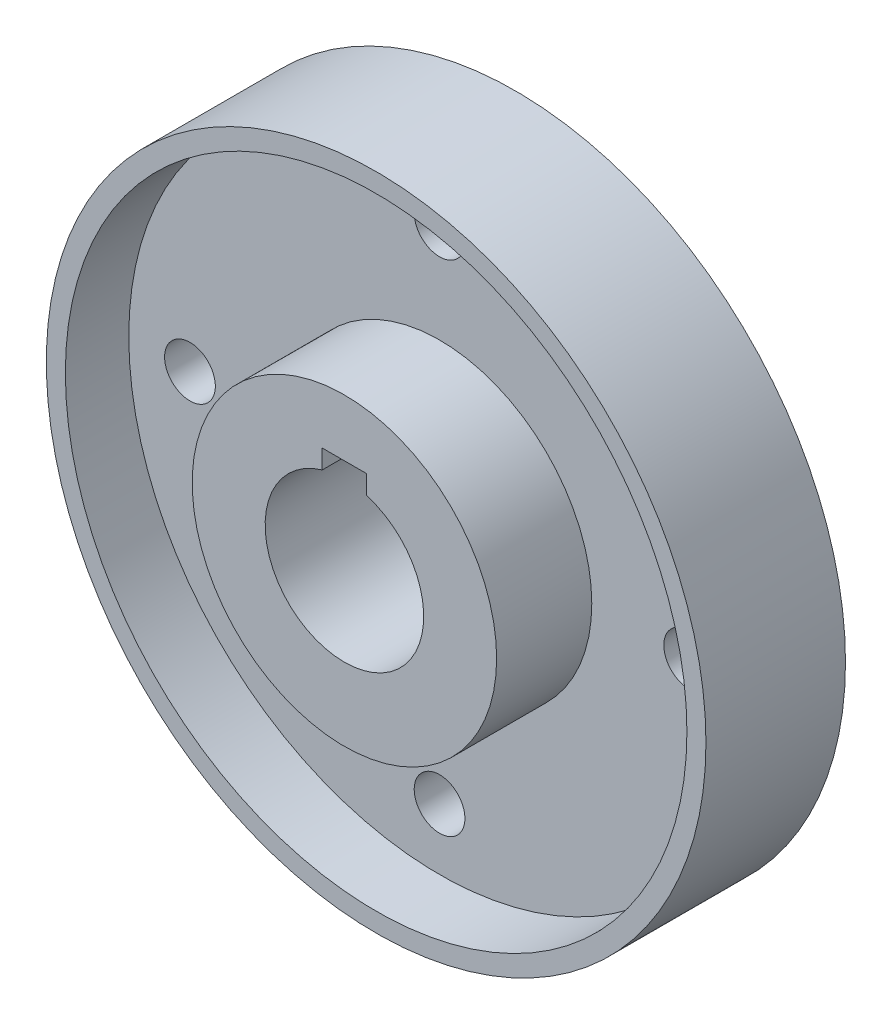
SolidWorks part; units mm, degrees
ref_plane "Front Plane" through (0, 0, 0) normal (0, 0, 1) x (1, 0, 0)
ref_plane "Top Plane" through (0, 0, 0) normal (0, 1, 0) x (1, 0, 0)
ref_plane "Right Plane" through (0, 0, 0) normal (1, 0, 0) x (0, 0, -1)
sketch "Sketch1" plane through (0, 0, 0) normal (1, 0, 0) x (0, 0, -1)
  line L0 (-44, 104) -> (0, 104)
  line L1 (0, 55) -> (0, -55) construction
  line L2 (0, 104) -> (0, 48)
  line L3 (0, 48) -> (3, 48)
  line L4 (3, 48) -> (3, 25)
  line L5 (3, 25) -> (-54, 25)
  line L6 (-54, 25) -> (-54, 48)
  line L7 (-54, 48) -> (-24, 48)
  line L8 (-24, 48) -> (-24, 98)
  line L9 (-24, 98) -> (-44, 98)
  line L10 (-44, 98) -> (-44, 104)
  line L11 (55, 0) -> (-55, 0) construction
  line L12 (-52.4965, 0) -> (46.7439, 0) construction
  dimension "D1" = 6
  dimension "D2" = 20
  dimension "D3" = 3
  dimension "D4" = 30
  dimension "D5" = 48
  dimension "D6" = 25
  dimension "D7" = 48
  dimension "D8" = 50
  dimension "D9" = 44
revolve "Revolve1" add sketch "Sketch1" angle 360 about L12
sketch "Sketch2" plane through (0, 0, 0) normal (0, 0, 1) x (1, 0, 0)
  line L0 (0, -55) -> (0, 55) construction
  line L1 (-7, 30) -> (7, 30)
  line L2 (-7, 30) -> (-7, 20)
  line L3 (-7, 20) -> (7, 20)
  line L4 (7, 30) -> (7, 20)
  line L5 (-7, 30) -> (7, 20) construction
  line L6 (-7, 20) -> (7, 30) construction
  circle A0 centre (0, 0) radius 25 construction
  point P0 (0, 25)
  dimension "D1" = 14
  dimension "D2" = 10
extrude "Cut-Extrude1" cut sketch "Sketch2" along normal mid plane 146
sketch "Sketch3" plane through (0, 0, 0) normal (0, 0, 1) x (1, 0, 0)
  line L0 (0, -29.7) -> (0, 29.7) construction
  circle A0 centre (0, 78.7044) radius 8
extrude "Cut-Extrude2" cut sketch "Sketch3" along normal blind 217
pattern_circular "CirPattern1" count 4 over 360 about axis through (0, 0, 0) along (0, 0, 1) of "Cut-Extrude2"
